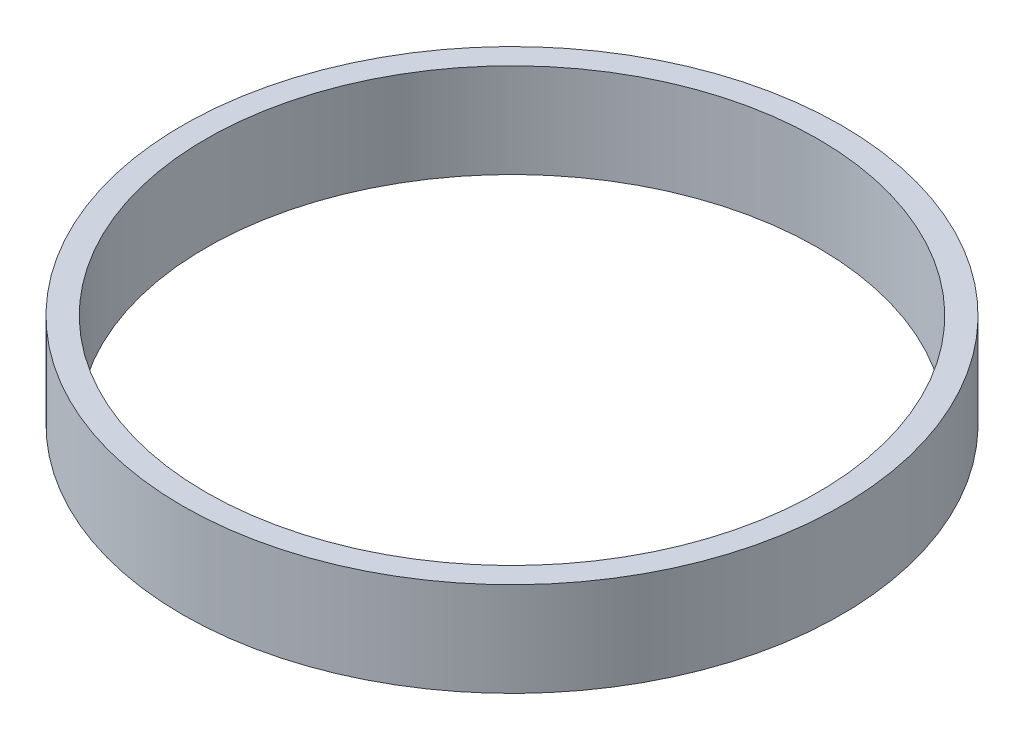
SolidWorks part; units mm, degrees
ref_plane "Płaszczyzna przednia" through (0, 0, 0) normal (0, 0, 1) x (1, 0, 0)
ref_plane "Płaszczyzna górna" through (0, 0, 0) normal (0, 1, 0) x (1, 0, 0)
ref_plane "Płaszczyzna prawa" through (0, 0, 0) normal (1, 0, 0) x (0, 0, -1)
sketch "Szkic1" plane through (0, 0, 0) normal (0, 1, 0) x (1, 0, 0)
  circle A0 centre (0, 0) radius 65
  circle A1 centre (0, 0) radius 70
  dimension "D1" = 130
  dimension "D2" = 140
extrude "Dodanie-wyciągnięcie1" add sketch "Szkic1" along normal mid plane 20
